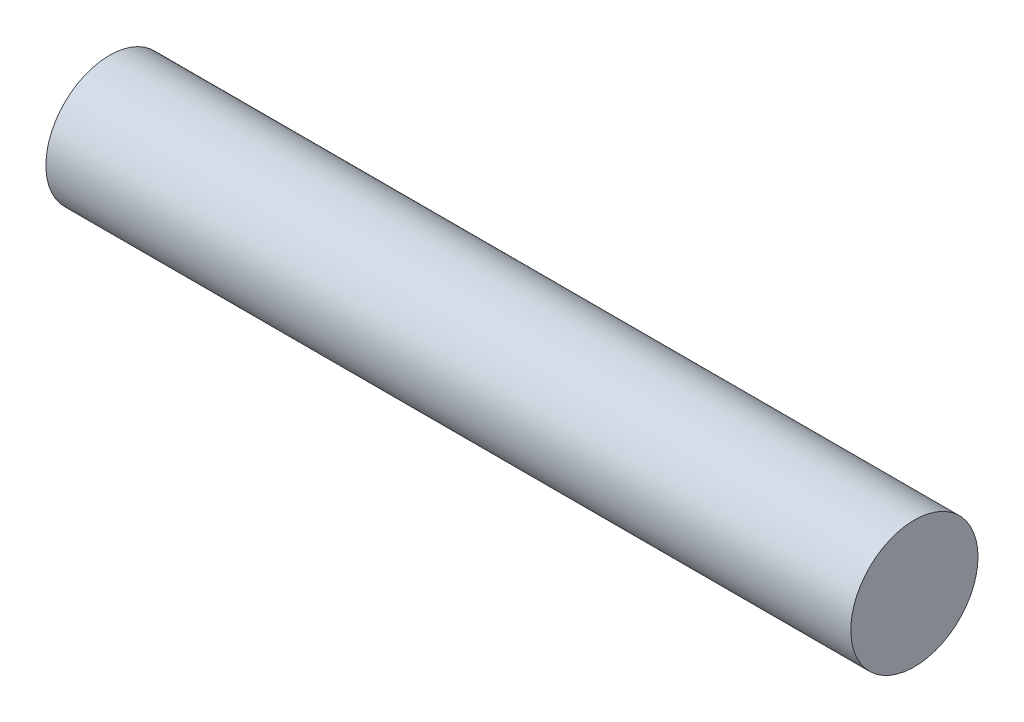
SolidWorks part; units mm, degrees
ref_plane "Front Plane" through (0, 0, 0) normal (0, 0, 1) x (1, 0, 0)
ref_plane "Top Plane" through (0, 0, 0) normal (0, 1, 0) x (1, 0, 0)
ref_plane "Right Plane" through (0, 0, 0) normal (1, 0, 0) x (0, 0, -1)
sketch "Sketch1" plane through (0, 0, 0) normal (1, 0, 0) x (0, 0, -1)
  circle A0 centre (0.2672, -0.1336) radius 6.0054
extrude "Boss-Extrude1" add sketch "Sketch1" along normal blind 76
